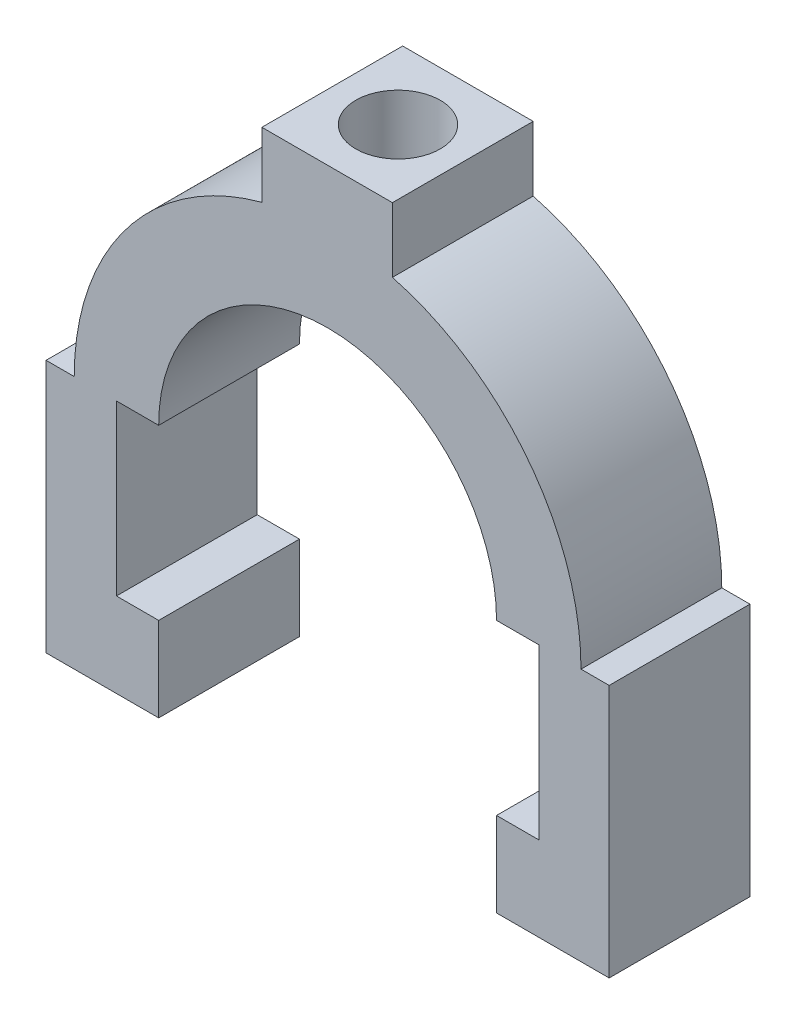
SolidWorks part; units mm, degrees
ref_plane "Ön Düzlem" through (0, 0, 0) normal (0, 0, 1) x (1, 0, 0)
ref_plane "Üst Düzlem" through (0, 0, 0) normal (0, 1, 0) x (1, 0, 0)
ref_plane "Sağ Düzlem" through (0, 0, 0) normal (1, 0, 0) x (0, 0, -1)
sketch "Çizim1" plane through (0, 0, 0) normal (0, 0, 1) x (1, 0, 0)
  line L0 (-30, 0) -> (-24, 0)
  line L1 (24, 0) -> (30, 0)
  line L3 (-40, 0) -> (-36, 0)
  line L4 (-40, 0) -> (-40, -36)
  line L5 (-40, -36) -> (-33.5425, -36)
  line L6 (-30, 0) -> (-30, -24)
  line L7 (-40, -36) -> (-24, -36)
  line L8 (-40, -36) -> (-40, -11.0389)
  line L9 (-30, -24) -> (-24, -24)
  line L10 (-24, -36) -> (-24, -24)
  line L11 (36, 0) -> (40, 0)
  line L12 (30, 0) -> (30, -24)
  line L13 (33, -36) -> (40, -36)
  line L14 (40, 0) -> (40, -36)
  line L15 (40, -36) -> (24, -36)
  line L16 (40, -36) -> (40, -11.0389)
  line L17 (30, -24) -> (24, -24)
  line L18 (24, -36) -> (24, -24)
  line L20 (-9.3375, 34.768) -> (-9.3375, 44)
  line L21 (-9.3375, 44) -> (9.2052, 44)
  line L22 (9.2052, 34.768) -> (9.2052, 44)
  arc A0 (24, 0) -> (-24, 0) centre (0, 0) ccw
  arc A1 (36, 0) -> (9.2052, 34.8032) centre (0, 0) ccw
  arc A2 (-9.3375, 34.768) -> (-36, 0) centre (0, 0) ccw
  dimension "D1" = 72
  dimension "D2" = 48
  dimension "D3" = 36
  dimension "D4" = 4
  dimension "D5" = 4
  dimension "D6" = 36
  dimension "D7" = 80
  dimension "D8" = 10
  dimension "D9" = 10
  dimension "D10" = 12
  dimension "D11" = 12
  dimension "D12" = 16
  dimension "D13" = 16
  dimension "D14" = 80
extrude "Yükseklik-Ekstrüzyon1" add sketch "Çizim1" along normal blind 20
sketch "Çizim2" plane through (0, 44, 0) normal (0, 1, 0) x (1, 0, 0)
  line L0 (-9.3375, -20) -> (9.2052, -20) construction
  circle A0 centre (0, -10) radius 6
  dimension "D1" = 12
  dimension "D2" = 10
extrude "Kes-Ekstrüzyon1" cut sketch "Çizim2" against normal through all
cosmetic thread "Kozmetik Diş Açma1" parameters "D2"=14
